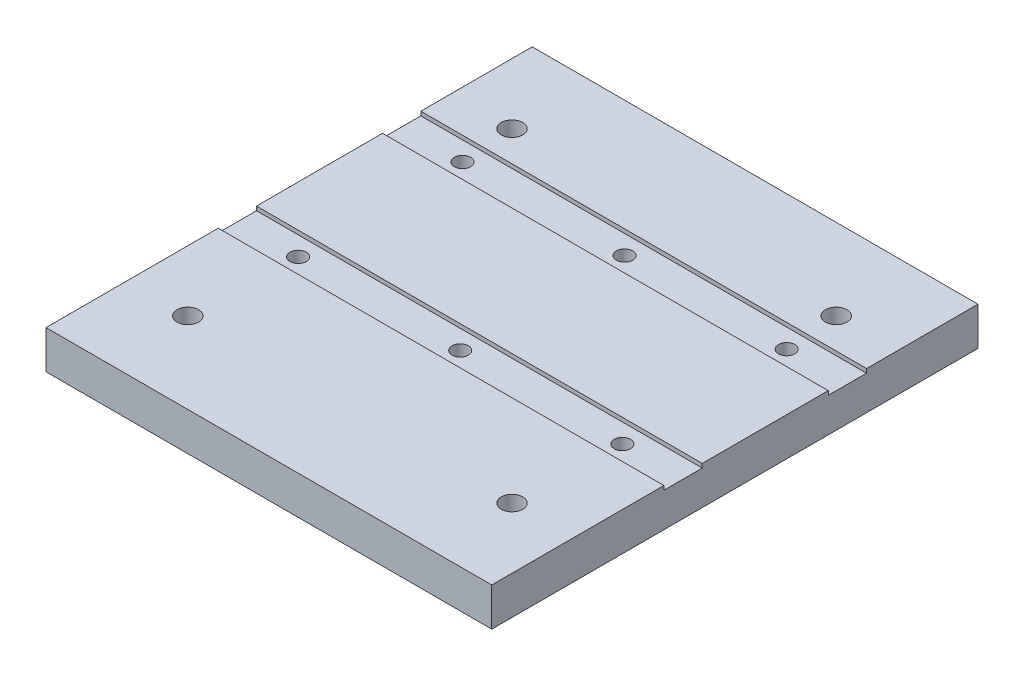
SolidWorks part; units mm, degrees
ref_plane "Front Plane" through (0, 0, 0) normal (0, 0, 1) x (1, 0, 0)
ref_plane "Top Plane" through (0, 0, 0) normal (0, 1, 0) x (1, 0, 0)
ref_plane "Right Plane" through (0, 0, 0) normal (1, 0, 0) x (0, 0, -1)
sketch "Sketch1" plane through (0, 0, 0) normal (0, 1, 0) x (1, 0, 0)
  line L7 (-69.85, -76.2) -> (69.85, -76.2)
  line L8 (-69.85, -76.2) -> (-69.85, 76.2)
  line L9 (-69.85, 76.2) -> (69.85, 76.2)
  line L10 (69.85, -76.2) -> (69.85, 76.2)
  line L11 (-69.85, -76.2) -> (69.85, 76.2) construction
  line L12 (-69.85, 76.2) -> (69.85, -76.2) construction
  point P0 (0, 0)
  point P6 (0, 0)
  dimension "D3" = 139.7
  dimension "D4" = 152.4
extrude "Boss-Extrude1" add sketch "Sketch1" along normal blind 12
sketch "Sketch2" plane through (0, 0, 0) normal (0, -1, 0) x (1, 0, 0)
  line L1 (-50.8, -50.8) -> (50.8, -50.8)
  line L2 (-50.8, -50.8) -> (-50.8, 50.8)
  line L3 (-50.8, 50.8) -> (50.8, 50.8)
  line L4 (50.8, -50.8) -> (50.8, 50.8)
  line L5 (-50.8, -50.8) -> (50.8, 50.8) construction
  line L6 (-50.8, 50.8) -> (50.8, -50.8) construction
  point P0 (0, 0)
  point P7 (-50.8, 50.8)
  point P8 (50.8, 50.8)
  point P9 (50.8, -50.8)
  point P10 (-50.8, -50.8)
  dimension "D1" = 101.6
  dimension "D2" = 101.6
hole_wizard "1/4 Clearance Hole1" positions "Sketch6" profile "Sketch7" hole size "1/4" standard "ANSI Inch" end condition through all
sketch "Sketch6" plane through (0, 12, 0) normal (0, 1, 0) x (1, 0, 0)
  point P0 (-50.8, 50.8)
  point P3 (50.8, 50.8)
  point P6 (50.8, -50.8)
  point P9 (-50.8, -50.8)
sketch "Sketch7" plane through (-50.8, 12, -50.8) normal (1, 0, 0) x (0, 0, 1)
  line L0 (0, 0) -> (0, 12)
  line L1 (0, 12) -> (3.3782, 12)
  line L2 (3.3782, 12) -> (3.3782, 0)
  line L5 (3.3782, 0) -> (0, 0)
  line L11 (0, -6.35) -> (0, 107.95) construction
  dimension "Thru Hole Dia." = 6.7564
  dimension "Thru Hole Depth" = 12
sketch "Sketch8" plane through (0, 12, 0) normal (0, 1, 0) x (1, 0, 0)
  line L0 (-69.85, 76.2) -> (-69.85, -76.2) construction
  line L1 (-69.85, 41.275) -> (69.85, 41.275)
  line L2 (-69.85, 41.275) -> (-69.85, 29.275)
  line L3 (-69.85, 29.275) -> (69.85, 29.275)
  line L4 (69.85, 41.275) -> (69.85, 29.275)
  line L5 (69.85, -76.2) -> (69.85, 76.2) construction
  line L12 (-69.85, -10.225) -> (69.85, -10.225)
  line L13 (-69.85, -10.225) -> (-69.85, -22.225)
  line L14 (-69.85, -22.225) -> (69.85, -22.225)
  line L15 (69.85, -10.225) -> (69.85, -22.225)
  circle A2 centre (-50.8, 50.8) radius 3.3782 construction
  circle A3 centre (-50.8, -50.8) radius 3.3782 construction
  dimension "D3" = 28.575
  dimension "D2" = 9.525
  dimension "D1" = 12
extrude "Cut-Extrude2" cut sketch "Sketch8" against normal blind 1.27
sketch "Sketch9" plane through (0, 10.73, 0) normal (0, 1, 0) x (1, 0, 0)
  line L0 (-69.85, 35.275) -> (69.85, 35.275) construction
  line L1 (-69.85, 41.275) -> (-69.85, 29.275) construction
  line L2 (69.85, 29.275) -> (69.85, 41.275) construction
  line L3 (-69.85, 9.525) -> (69.85, 9.525) construction
  line L4 (-69.85, 29.275) -> (-69.85, -10.225) construction
  line L5 (69.85, -10.225) -> (69.85, 29.275) construction
  point P6 (-50.8, 35.275)
  point P7 (0, 35.275)
  point P8 (50.8, 35.275)
  point P9 (50.8, -16.225)
  point P10 (0, -16.225)
  point P11 (-50.8, -16.225)
  dimension "D1" = 19.05
  dimension "D2" = 19.05
hole_wizard "CBORE for #10 Socket Head Cap Screw1" positions "Sketch10" profile "Sketch11" counterbore size "#10" standard "ANSI Inch" end condition through all
sketch "Sketch10" plane through (0, 0, 0) normal (0, -1, 0) x (-1, 0, 0)
  point P0 (-50.8, 35.275)
  point P3 (0, 35.275)
  point P6 (50.8, 35.275)
  point P9 (50.8, -16.225)
  point P12 (0, -16.225)
  point P15 (-50.8, -16.225)
sketch "Sketch11" plane through (50.8, 0, -35.275) normal (1, 0, 0) x (0, 0, -1)
  line L0 (0, 0) -> (0, 12)
  line L1 (0, 12) -> (2.5527, 12)
  line L3 (2.5527, 12) -> (2.5527, 4.826)
  line L4 (2.5527, 4.826) -> (4.7625, 4.826)
  line L5 (4.7625, 4.826) -> (4.7625, 0)
  line L7 (4.7625, 0) -> (0, 0)
  line L11 (0, -6.35) -> (0, 107.95) construction
  dimension "Thru Hole Dia." = 5.1054
  dimension "Thru Hole Depth" = 12
  dimension "C'Bore Dia." = 9.525
  dimension "C'Bore Depth" = 4.826
